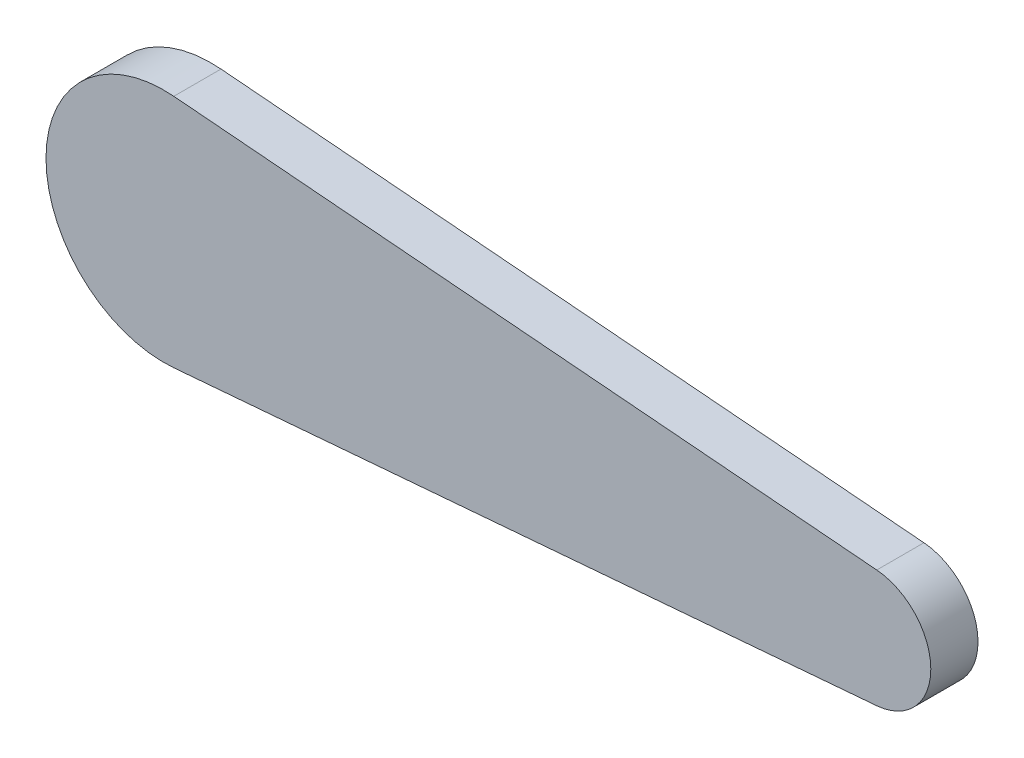
SolidWorks part; units mm, degrees
ref_plane "前视基准面" through (0, 0, 0) normal (0, 0, 1) x (1, 0, 0)
ref_plane "上视基准面" through (0, 0, 0) normal (0, 1, 0) x (1, 0, 0)
ref_plane "右视基准面" through (0, 0, 0) normal (1, 0, 0) x (0, 0, -1)
sketch "草图1" plane through (0, 0, 0) normal (0, 0, 1) x (1, 0, 0)
  line L0 (4.1667, 49.8261) -> (302.0833, 24.913)
  line L1 (4.1667, -49.8261) -> (302.0833, -24.913)
  circle A0 centre (0, 0) radius 50
  circle A1 centre (300, 0) radius 25
  dimension "D1" = 100
  dimension "D2" = 50
  dimension "D3" = 300
extrude "凸台-拉伸1" add sketch "草图1" along normal blind 20 contours A0 | A1 L0 A0 L1 | A1
sketch "草图2" plane through (0, 0, 0) normal (0, 0, -1) x (-1, 0, 0)
  circle A0 centre (0, 0) radius 25
  dimension "D1" = 50
extrude "凸台-拉伸2" add sketch "草图2" along normal blind 20
